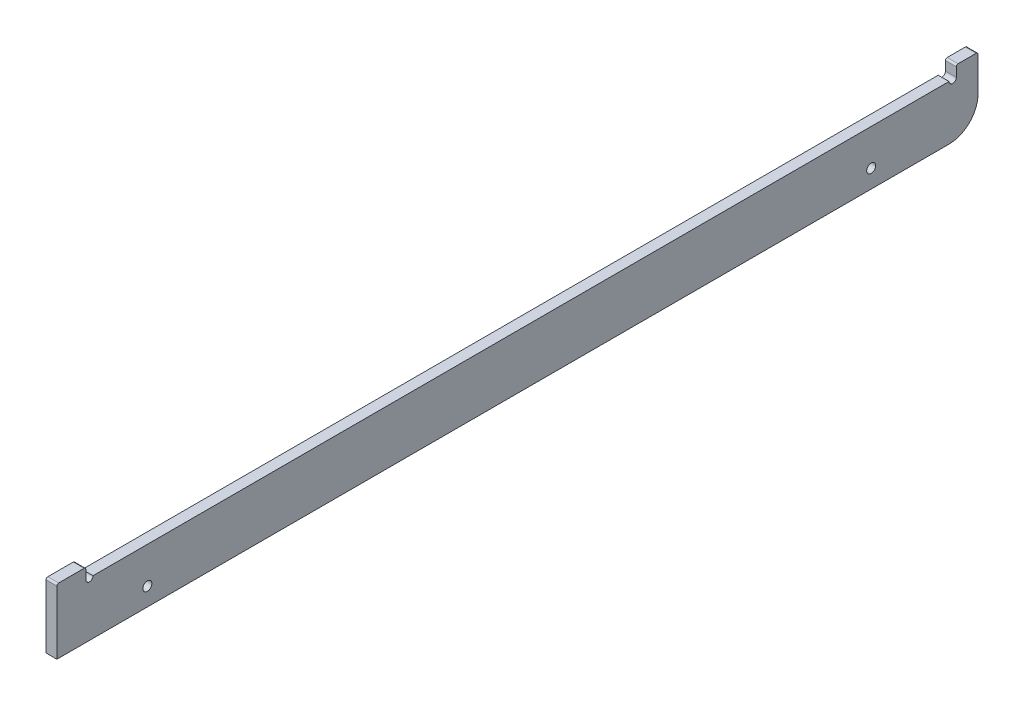
SolidWorks part; units mm, degrees
ref_plane "정면" through (0, 0, 0) normal (0, 0, 1) x (1, 0, 0)
ref_plane "윗면" through (0, 0, 0) normal (0, 1, 0) x (1, 0, 0)
ref_plane "우측면" through (0, 0, 0) normal (1, 0, 0) x (0, 0, -1)
sketch "스케치1" plane through (0, 0, 0) normal (1, 0, 0) x (0, 0, -1)
  line L1 (0, 0) -> (254.5, 0)
  line L2 (0, 0) -> (0, 15)
  line L3 (0, 15) -> (254.5, 15)
  line L4 (254.5, 0) -> (254.5, 15)
  dimension "D1" = 254.5
  dimension "D2" = 15
extrude "보스-돌출1" add sketch "스케치1" along normal blind 3
sketch "스케치2" plane through (3, 0, 0) normal (1, 0, 0) x (0, 0, -1)
  line L0 (-2.5, 18) -> (292.5, 18) construction
  line L1 (0, 15) -> (8, 15)
  line L2 (0, 15) -> (0, 18)
  line L3 (0, 18) -> (8, 18)
  line L4 (8, 15) -> (8, 18)
  line L6 (254.5, 15) -> (248.5, 15)
  line L7 (254.5, 15) -> (254.5, 18)
  line L8 (254.5, 18) -> (248.5, 18)
  line L9 (248.5, 15) -> (248.5, 18)
  dimension "D1" = 6
  dimension "D2" = 8
extrude "보스-돌출2" add sketch "스케치2" against normal blind 3
sketch "스케치3" plane through (3, 0, 0) normal (1, 0, 0) x (0, 0, -1)
  line L4 (248.5, 15) -> (8, 15) construction
  line L5 (8, 15) -> (8, 18) construction
  line L6 (248.5, 18) -> (248.5, 15) construction
  circle A0 centre (9, 15) radius 1
  circle A1 centre (247.5, 15) radius 1
  dimension "D1" = 2
extrude "컷-돌출1" cut sketch "스케치3" against normal blind 3
fillet "필렛1" radius 0.5 4 edges at (1.5, 18, -254.5) (1.5, 18, -248.5) (1.5, 18, -8) (1.5, 18, 0)
sketch "스케치4" plane through (3, 0, 0) normal (1, 0, 0) x (0, 0, -1)
  line L0 (28.05, 5) -> (25, 5) construction
  line L1 (25, 5) -> (21.95, 5) construction
  line L2 (228.05, 5) -> (225, 5) construction
  line L3 (225, 5) -> (221.95, 5) construction
  arc A0 (26.5, 3.45) -> (26.5, 6.55) centre (26.5, 5) ccw construction
  arc A1 (23.5, 6.55) -> (23.5, 3.45) centre (23.5, 5) ccw construction
  arc A2 (226.5, 3.45) -> (226.5, 6.55) centre (226.5, 5) ccw construction
  arc A3 (223.5, 6.55) -> (223.5, 3.45) centre (223.5, 5) ccw construction
  circle A4 centre (225, 5) radius 1.25
  circle A5 centre (25, 5) radius 1.25
  dimension "D1" = 2.5
extrude "컷-돌출2" cut sketch "스케치4" against normal blind 10
fillet "필렛2" radius 8 1 edges at (1.5, 0, -254.5)
